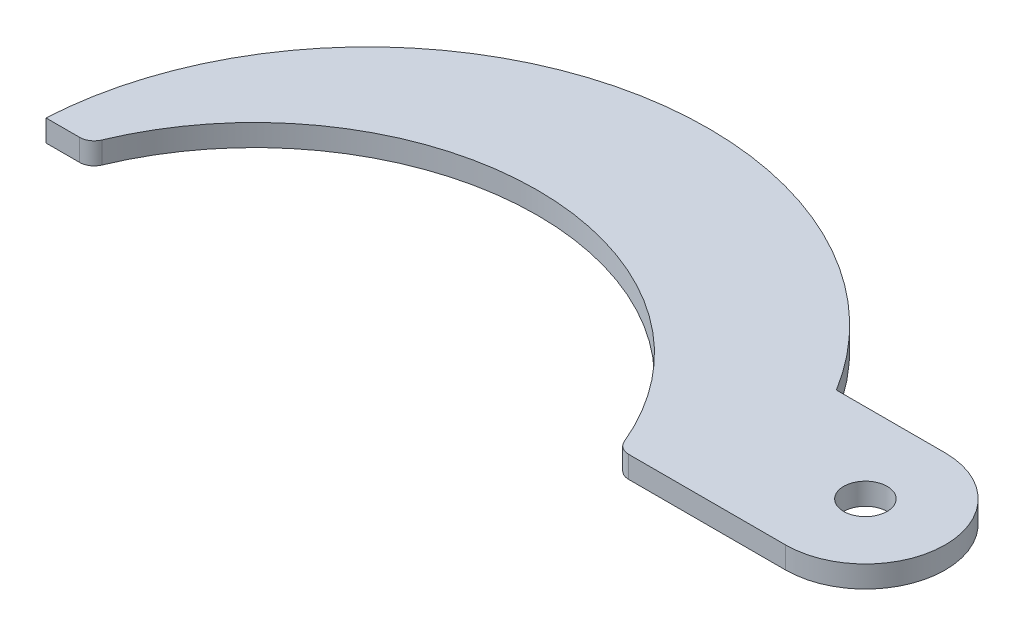
SolidWorks part; units mm, degrees
material "1.0420 (G200)"
ref_plane "Alzado" through (0, 0, 0) normal (0, 0, 1) x (1, 0, 0)
ref_plane "Planta" through (0, 0, 0) normal (0, 1, 0) x (1, 0, 0)
ref_plane "Vista lateral" through (0, 0, 0) normal (1, 0, 0) x (0, 0, -1)
sketch "Croquis1" plane through (0, 0, 0) normal (0, 1, 0) x (1, 0, 0)
  line L0 (59.9689, -6.4664) -> (82.9689, -6.4664)
  line L1 (82.9689, 15.5336) -> (67.9689, 15.5336)
  line L2 (-19.0311, -6.4664) -> (-13.0311, -6.4664)
  line L3 (70.7091, 15.5336) -> (-70.7767, 15.5336) construction
  arc A0 (82.9689, -6.4664) -> (82.9689, 15.5336) centre (82.9689, 4.5336) ccw
  arc A2 (67.9689, 15.5336) -> (-19.0311, -6.4664) centre (27.8989, -9.0305) ccw
  arc A3 (59.9689, -6.4664) -> (-13.0311, -6.4664) centre (23.4689, -20.205) ccw
  circle A4 centre (82.9689, 4.5336) radius 3
  dimension "D5" = 47
  dimension "D6" = 39
  dimension "D8" = 6
  dimension "D1" = 22
  dimension "D2" = 15
  dimension "D3" = 23
  dimension "D4" = 6
  dimension "D7" = 102
extrude "Saliente-Extruir1" add sketch "Croquis1" along normal blind 3
fillet "Redondeo1" radius 2 1 edges at (59.9689, 1.5, 6.4664)
fillet "Redondeo2" radius 2 1 edges at (-13.0311, 1.5, 6.4664)
